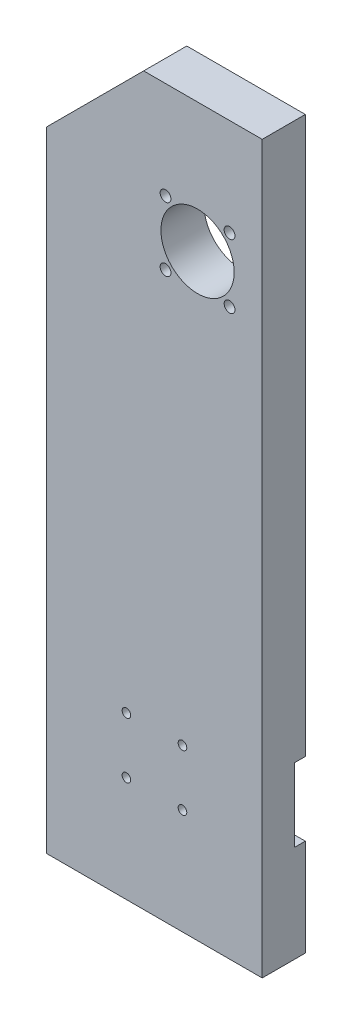
SolidWorks part; units mm, degrees
ref_plane "Front Plane" through (0, 0, 0) normal (0, 0, 1) x (1, 0, 0)
ref_plane "Top Plane" through (0, 0, 0) normal (0, 1, 0) x (1, 0, 0)
ref_plane "Right Plane" through (0, 0, 0) normal (1, 0, 0) x (0, 0, -1)
sketch "Sketch1" plane through (0, 0, 0) normal (0, 0, 1) x (1, 0, 0)
  line L0 (67.7045, 560.5004) -> (52.8553, 575.3496) construction
  line L1 (67.7045, 560.5004) -> (46.7045, 560.5004) construction
  line L2 (67.7045, 560.5004) -> (67.7045, 581.5004) construction
  line L3 (47.7045, 545.8558) -> (47.7045, 439.2537) construction
  line L4 (7.7288, 345.5004) -> (63.5732, 345.5004) construction
  line L5 (97.7045, 283.5004) -> (-2.2955, 283.5004)
  line L6 (97.7045, 283.5004) -> (97.7045, 620.5004)
  line L7 (97.7045, 620.5004) -> (-2.2955, 620.5004)
  line L8 (-2.2955, 283.5004) -> (-2.2955, 620.5004)
  line L9 (97.7045, 283.5004) -> (-2.2955, 620.5004) construction
  line L10 (97.7045, 620.5004) -> (-2.2955, 283.5004) construction
  circle A0 centre (67.7045, 560.5004) radius 17
  circle A1 centre (67.7045, 560.5004) radius 21 construction
  circle A2 centre (82.5538, 575.3496) radius 2.5
  circle A3 centre (82.5538, 545.6511) radius 2.5
  circle A4 centre (52.8553, 545.6511) radius 2.5
  circle A5 centre (52.8553, 575.3496) radius 2.5
  circle A6 centre (34.7045, 358.5004) radius 2
  circle A7 centre (60.7045, 358.5004) radius 2
  circle A8 centre (60.7045, 332.5004) radius 2
  circle A9 centre (34.7045, 332.5004) radius 2
  point P5 (52.8553, 575.3496)
  point P6 (82.5538, 575.3496)
  point P7 (82.5538, 545.6511)
  point P8 (52.8553, 545.6511)
  point P19 (47.7045, 452.0004)
  point P34 (0, 0)
  point P35 (0, 0)
  dimension "D2" = 5
  dimension "D3" = 34
  dimension "D4" = 42
  dimension "D10" = 4
  dimension "D1" = 45
  dimension "D5" = 337
  dimension "D6" = 100
  dimension "D7" = 60
  dimension "D8" = 13
  dimension "D9" = 13
  dimension "D11" = 62
  dimension "D12" = 30
extrude "Boss-Extrude1" add sketch "Sketch1" along normal blind 20
chamfer "Chamfer1" distance 45 angle 45 1 edges at (-2.2955, 620.5004, 10)
sketch "Sketch2" plane through (0, 0, 0) normal (0, 0, 1) x (1, 0, 0)
  line L0 (60.7045, 358.5004) -> (34.7045, 332.5004) construction
  line L1 (34.7045, 358.5004) -> (60.7045, 332.5004) construction
  line L3 (97.7045, 328.5004) -> (-2.2955, 328.5004)
  line L4 (97.7045, 328.5004) -> (97.7045, 362.5004)
  line L5 (97.7045, 362.5004) -> (-2.2955, 362.5004)
  line L6 (-2.2955, 328.5004) -> (-2.2955, 362.5004)
  line L7 (97.7045, 328.5004) -> (-2.2955, 362.5004) construction
  line L8 (97.7045, 362.5004) -> (-2.2955, 328.5004) construction
  point P8 (47.7045, 345.5004)
  point P9 (47.7045, 345.5004)
  dimension "D1" = 100
  dimension "D2" = 34
extrude "Cut-Extrude1" cut sketch "Sketch2" along normal blind 5
